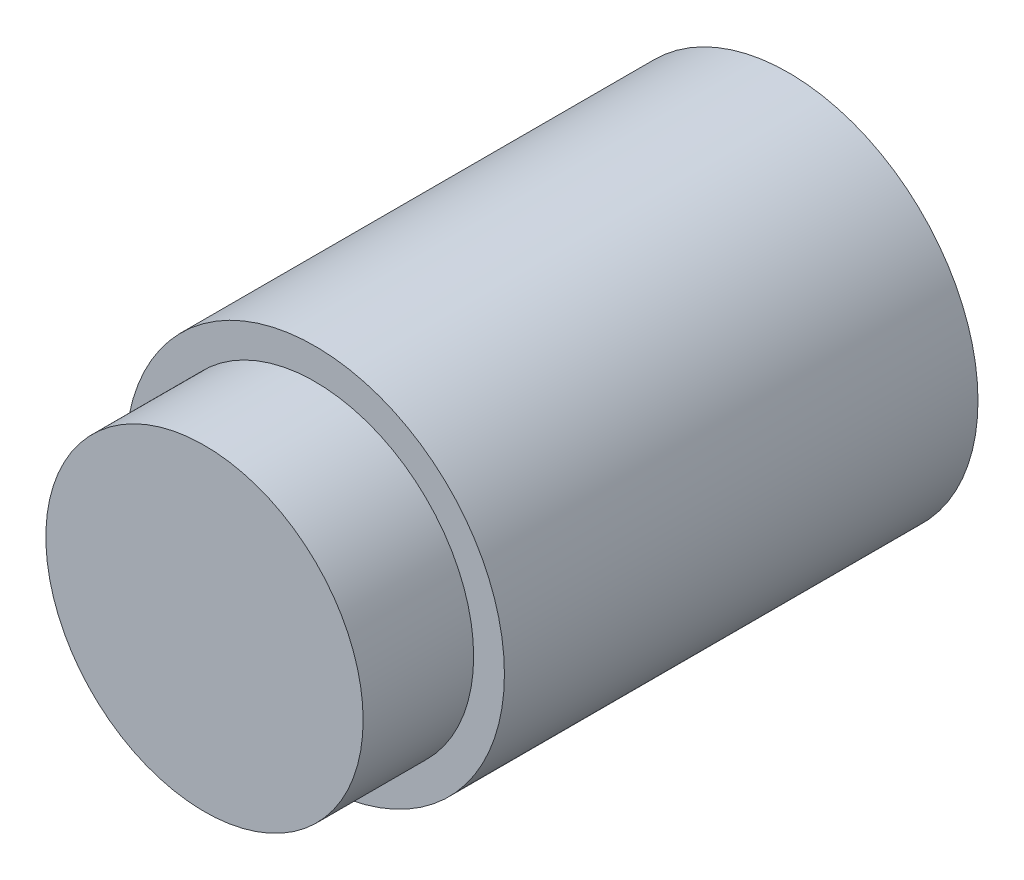
SolidWorks part; units mm, degrees
ref_plane "Front Plane" through (0, 0, 0) normal (1, 0, 0) x (0, 1, 0)
ref_plane "Top Plane" through (0, 0, 0) normal (0, 0, 1) x (0, 1, 0)
ref_plane "Right Plane" through (0, 0, 0) normal (0, 1, 0) x (-1, 0, 0)
sketch "Sketch1" plane through (0, 0, 0) normal (0, 0, 1) x (0, 1, 0)
  circle A0 centre (0, 0) radius 6
  dimension "D1" = 12
extrude "Boss-Extrude1" add sketch "Sketch1" along normal blind 15 contours A0
sketch "Sketch2" plane through (0, 0, 15) normal (0, 0, 1) x (1, 0, 0)
  circle A0 centre (0, 0) radius 5.025
  dimension "D1" = 10.05
extrude "Boss-Extrude2" add sketch "Sketch2" along normal blind 3.5
